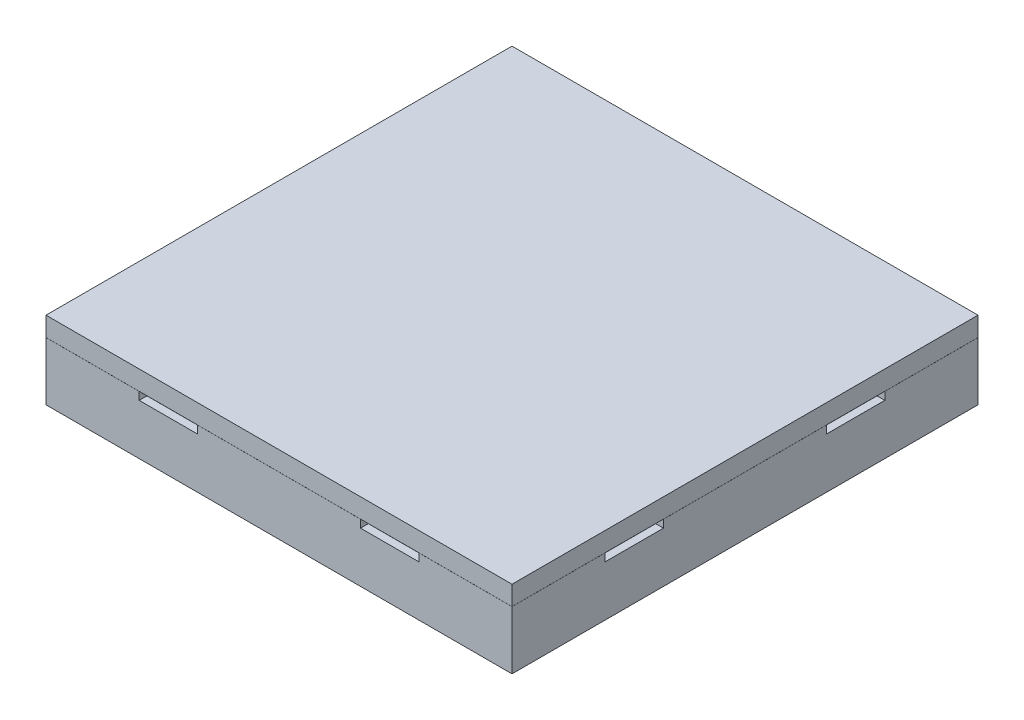
SolidWorks part; units mm, degrees
ref_plane "前视基准面" through (0, 0, 0) normal (0, 0, 1) x (1, 0, 0)
ref_plane "上视基准面" through (0, 0, 0) normal (0, 1, 0) x (1, 0, 0)
ref_plane "右视基准面" through (0, 0, 0) normal (1, 0, 0) x (0, 0, -1)
other "Configuration Table"
sketch "草图1" plane through (0, 0, 0) normal (0, 1, 0) x (1, 0, 0)
  line L5 (0, 0) -> (-600, 0)
  line L6 (0, 0) -> (0, -600)
  line L7 (0, -600) -> (-600, -600)
  line L8 (-600, 0) -> (-600, -600)
  dimension "D1" = 600
extrude "凸台-拉伸1" add sketch "草图1" along normal blind 200
sketch "草图2" plane through (-600, 0, 0) normal (-1, 0, 0) x (0, 0, 1)
  line L0 (600, 150.2) -> (0, 150.2)
  line L1 (600, 200) -> (600, 0) construction
  line L2 (0, 200) -> (0, 0) construction
  line L3 (0, 150.2) -> (0, 150)
  line L4 (0, 150) -> (210, 150)
  line L5 (210, 150) -> (210, 130)
  line L6 (210, 130) -> (360, 130)
  line L7 (360, 130) -> (360, 150)
  line L8 (360, 150) -> (600, 150)
  line L13 (600, 150) -> (600, 150.2)
  line L14 (0, 0) -> (600, 0) construction
  dimension "D1" = 0.2
  dimension "D2" = 20
  dimension "D3" = 150
  dimension "D4" = 240
  dimension "D5" = 210
  dimension "D6" = 150
extrude "切除-拉伸1" cut sketch "草图2" against normal blind 20
sketch "草图3" plane through (0, 0, 600) normal (0, 0, 1) x (1, 0, 0)
  line L0 (-580, 150.2) -> (-580, 150)
  line L1 (-580, 150) -> (-360, 150)
  line L2 (-360, 150) -> (-360, 130)
  line L3 (-360, 130) -> (-210, 130)
  line L4 (-210, 130) -> (-210, 150)
  line L5 (-210, 150) -> (0, 150)
  line L6 (0, 200) -> (0, 0) construction
  line L7 (0, 150) -> (0, 150.2)
  line L8 (0, 150.2) -> (-580, 150.2)
  line L9 (-600, 150) -> (-600, 0) construction
  dimension "D1" = 20
  dimension "D2" = 150
  dimension "D3" = 240
extrude "切除-拉伸2" cut sketch "草图3" against normal blind 20
mirror "镜向1" about plane through (0, 200, 0) normal (0, 0, 1) of bodies 108
mirror "镜向2" about plane through (0, 200, 0) normal (-1, 0, 0) of bodies 109
